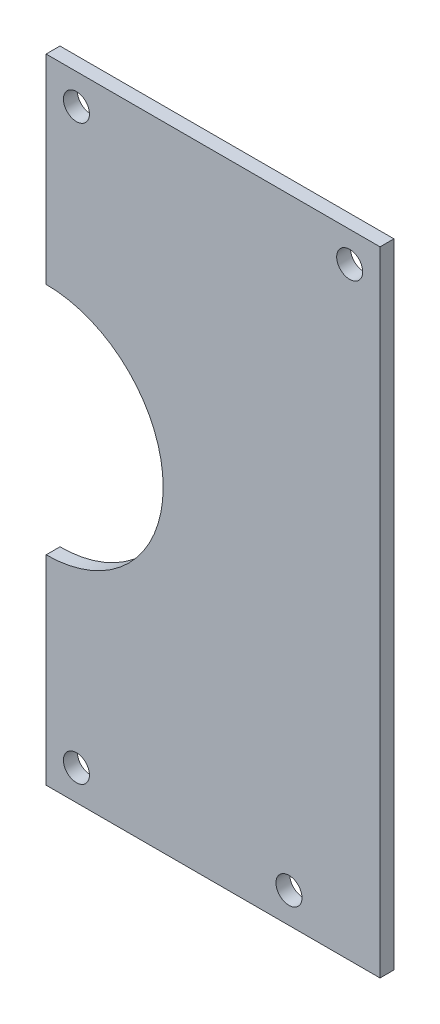
SolidWorks part; units mm, degrees
ref_plane "Front Plane" through (0, 0, 0) normal (0, 0, 1) x (1, 0, 0)
ref_plane "Top Plane" through (0, 0, 0) normal (0, 1, 0) x (1, 0, 0)
ref_plane "Right Plane" through (0, 0, 0) normal (1, 0, 0) x (0, 0, -1)
sketch "Sketch1" plane through (0, 0, 0) normal (0, 0, 1) x (1, 0, 0)
  line L0 (0, -50) -> (0, 50) construction
  line L1 (-50, 0) -> (50, 0) construction
  line L5 (50, 50) -> (-50, 50)
  line L6 (50, 50) -> (50, -50)
  line L7 (50, -50) -> (-50, -50)
  line L8 (-50, 50) -> (-50, -50)
  circle A0 centre (0, 0) radius 11
  point P10 (0, 0)
sketch "Sketch2" plane through (0, 0, 0) normal (0, 0, 1) x (1, 0, 0)
  line L1 (-50, 50) -> (-41.5, 50)
  line L2 (-50, 50) -> (-50, 41.5)
  line L3 (-50, 41.5) -> (-41.5, 41.5)
  line L4 (-41.5, 50) -> (-41.5, 41.5)
  line L5 (50, 41.5) -> (41.5, 41.5)
  line L6 (41.5, 50) -> (41.5, 41.5)
  line L7 (50, 50) -> (41.5, 50)
  line L8 (50, 50) -> (50, 41.5)
  line L10 (50, -50) -> (50, -41.5)
  line L11 (50, -50) -> (41.5, -50)
  line L12 (41.5, -50) -> (41.5, -41.5)
  line L13 (50, -41.5) -> (41.5, -41.5)
  line L14 (-50, -41.5) -> (-41.5, -41.5)
  line L15 (-41.5, -50) -> (-41.5, -41.5)
  line L16 (-50, -50) -> (-41.5, -50)
  line L17 (-50, -50) -> (-50, -41.5)
sketch "Sketch3" plane through (0, 0, 0) normal (0, 0, 1) x (1, 0, 0)
  line L0 (11, 0) -> (13.5, 0) construction
  line L1 (-50, 0) -> (50, 0) construction
  line L3 (13.5, 36.5) -> (38.5, 36.5)
  line L4 (13.5, -36.5) -> (38.5, -36.5)
  line L5 (38.5, -36.5) -> (38.5, 36.5)
  line L6 (0, 11) -> (0, 13.5) construction
  line L7 (0, -50) -> (0, 50) construction
  line L8 (55, 0) -> (-55, 0) construction
  line L9 (0, -11) -> (0, -13.5) construction
  line L10 (13.5, -36.5) -> (0, -36.5)
  line L11 (0, -36.5) -> (0, -13.5)
  line L12 (13.5, 36.5) -> (0, 36.5)
  line L13 (0, 36.5) -> (0, 13.5)
  circle A0 centre (0, 0) radius 11 construction
  arc A1 (0, 13.5) -> (0, -13.5) centre (0, 0) cw
extrude "Boss-Extrude1" add sketch "Sketch3" against normal blind 1.6
sketch "Sketch4" plane through (0, 0, 0) normal (0, 0, 1) x (1, 0, 0)
  line L0 (38.5, -36.5) -> (38.5, -33) construction
  line L1 (38.5, -36.5) -> (38.5, 36.5) construction
  line L2 (35, -33) -> (28, -33) construction
  line L3 (0.88, 0) -> (-0.88, 0) construction
  line L4 (0, -36.5) -> (0, -33) construction
  line L5 (0, -36.5) -> (38.5, -36.5) construction
  line L6 (0, -50) -> (0, 50) construction
  line L7 (0, -33) -> (3.5, -33) construction
  line L8 (0, 0) -> (3.5, 0) construction
  line L9 (-50, 0) -> (50, 0) construction
  line L10 (3.5, 0) -> (3.5, -33) construction
  line L11 (3.5, -33) -> (35, -33) construction
  circle A1 centre (35, 33) radius 1.5
  circle A2 centre (3.5, -33) radius 1.5
  circle A3 centre (3.5, 33) radius 1.5
  circle A4 centre (28, -33) radius 1.5
extrude "Cut-Extrude1" cut sketch "Sketch4" against normal through all
